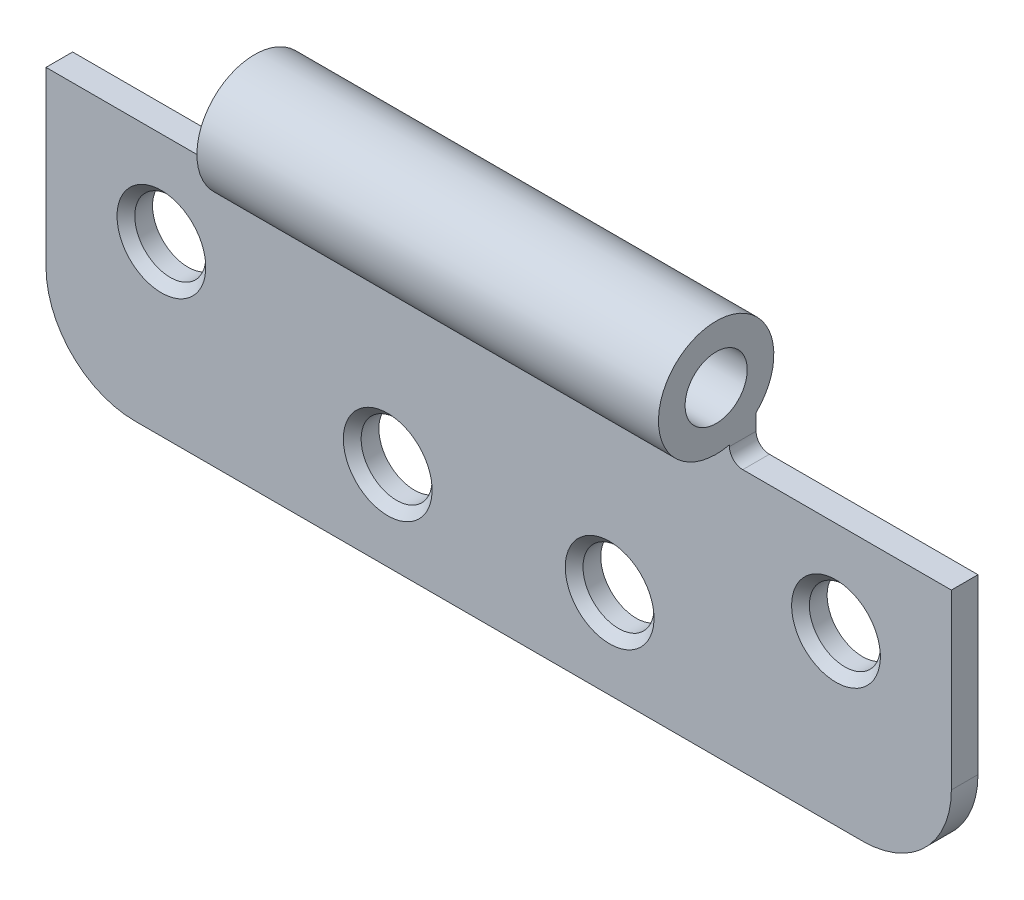
SolidWorks part; units mm, degrees
ref_plane "Front Plane" through (0, 0, 0) normal (0, 0, 1) x (1, 0, 0)
ref_plane "Top Plane" through (0, 0, 0) normal (0, 1, 0) x (1, 0, 0)
ref_plane "Right Plane" through (0, 0, 0) normal (1, 0, 0) x (0, 0, -1)
sketch "Sketch1" plane through (0, 0, 0) normal (0, 0, 1) x (1, 0, 0)
  line L0 (27.5, 29.5) -> (51, 29.5)
  line L1 (-41, 0) -> (41, 0)
  line L2 (-51, 10) -> (-51, 29.5)
  line L3 (-51, 29.5) -> (-27.5, 29.5)
  line L4 (51, 10) -> (51, 29.5)
  line L6 (-26, 31) -> (-26, 37.5)
  line L7 (-26, 37.5) -> (26, 37.5)
  line L8 (26, 31) -> (26, 37.5)
  arc A0 (51, 10) -> (41, 0) centre (41, 10) cw
  arc A1 (-51, 10) -> (-41, 0) centre (-41, 10) ccw
  arc A2 (27.5, 29.5) -> (26, 31) centre (27.5, 31) cw
  arc A3 (-27.5, 29.5) -> (-26, 31) centre (-27.5, 31) ccw
  circle A4 centre (-38, 19) radius 4
  circle A5 centre (38, 19) radius 4
  circle A6 centre (-12.5, 10) radius 4
  circle A7 centre (12.5, 10) radius 4
  point P8 (0, 0)
  point P10 (0, 37.5)
  point P13 (51, 0)
  point P16 (-51, 0)
  dimension "D5" = 10
  dimension "D6" = 1.5
  dimension "D7" = 8
  dimension "D8" = 18.5
  dimension "D9" = 27.5
  dimension "D10" = 25
  dimension "D12" = 76
  dimension "D1" = 29.5
  dimension "D2" = 102
  dimension "D3" = 37.5
  dimension "D4" = 52
  dimension "D11" = 12.5
  dimension "D13" = 38
extrude "Boss-Extrude1" add sketch "Sketch1" along normal blind 3
sketch "Sketch2" plane through (-26, 0, 0) normal (-1, 0, 0) x (0, 0, 1)
  line L4 (0, 37.5) -> (0, 31) construction
  circle A1 centre (4.5, 37.5) radius 6.5
  dimension "D1" = 13
  dimension "D2" = 4.5
extrude "Boss-Extrude2" add sketch "Sketch2" against normal up to surface (52 mm away) up to face at (26, 34.25, 1.5)
sketch "Sketch3" plane through (-26, 0, 0) normal (-1, 0, 0) x (0, 0, 1)
  circle A0 centre (4.5, 37.5) radius 3.5
  dimension "D1" = 7
extrude "Cut-Extrude1" cut sketch "Sketch3" against normal through all
chamfer "Chamfer1" distance 1 angle 45 4 edges at (42, 19, 3) (16.5, 10, 3) (-8.5, 10, 3) (-34, 19, 3)
